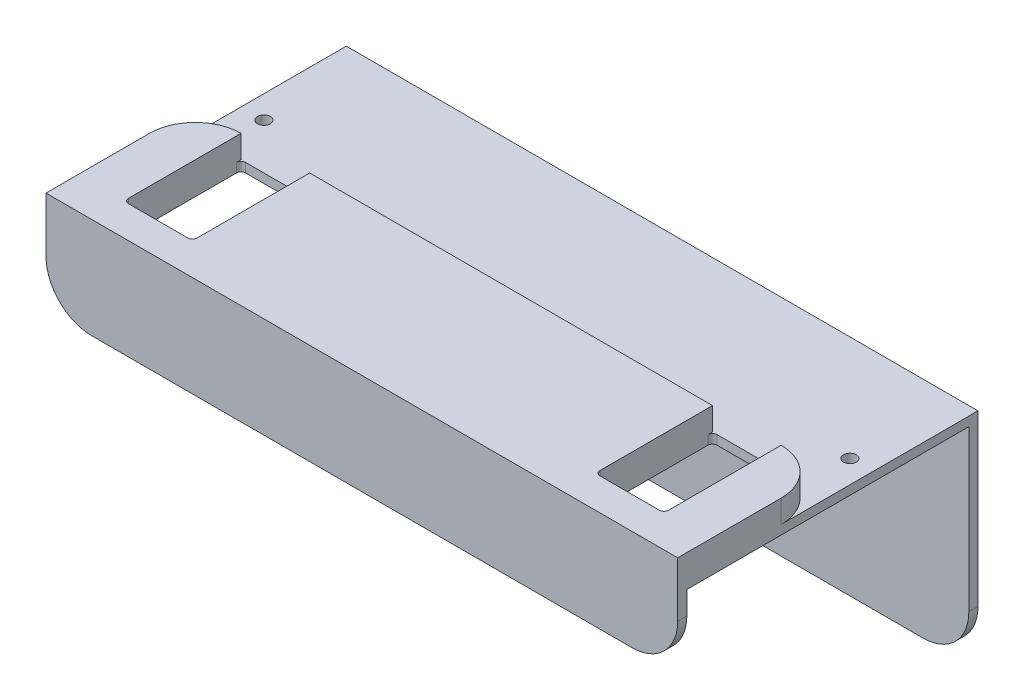
SolidWorks part; units mm, degrees
ref_plane "前视基准面" through (0, 0, 0) normal (0, 0, 1) x (1, 0, 0)
ref_plane "上视基准面" through (0, 0, 0) normal (0, 1, 0) x (1, 0, 0)
ref_plane "右视基准面" through (0, 0, 0) normal (1, 0, 0) x (0, 0, -1)
other "Configuration Table"
sketch "草图1" plane through (0, 0, 0) normal (0, 1, 0) x (1, 0, 0)
  line L0 (-64, 9.8) -> (64, 9.8) construction
  line L1 (-69, -32.8) -> (69, -32.8)
  line L2 (-69, -32.8) -> (-69, 32.8)
  line L3 (-69, 32.8) -> (69, 32.8)
  line L4 (69, -32.8) -> (69, 32.8)
  line L5 (-69, -32.8) -> (69, 32.8) construction
  line L6 (-69, 32.8) -> (69, -32.8) construction
  line L7 (0, 9.8) -> (0, 32.8) construction
  circle A0 centre (-64, 9.8) radius 1.4
  circle A1 centre (64, 9.8) radius 1.4
  point P0 (0, 0)
  dimension "D3" = 2.8
  dimension "D4" = 2.8
  dimension "D5" = 128
  dimension "D6" = 23
  dimension "D1" = 138
  dimension "D2" = 65.6
extrude "凸台-拉伸1" add sketch "草图1" along normal blind 2
sketch "草图2" plane through (0, 2, 0) normal (0, 1, 0) x (1, 0, 0)
  line L0 (69, -32.8) -> (69, 32.8) construction
  line L1 (-69, -32.8) -> (69, -32.8)
  line L2 (-69, -32.8) -> (-69, -0.2)
  line L3 (-69, -0.2) -> (69, -0.2)
  line L4 (69, -32.8) -> (69, -0.2)
  line L5 (69, 32.8) -> (-69, 32.8) construction
  dimension "D1" = 33
extrude "凸台-拉伸2" add sketch "草图2" along normal blind 5
sketch "草图3" plane through (0, 0, 0) normal (0, -1, 0) x (1, 0, 0)
  line L0 (-69, -32.8) -> (-69, 32.8) construction
  line L2 (-69, -30.8) -> (69, -30.8)
  line L3 (-69, -30.8) -> (-69, -32.8)
  line L4 (-69, -32.8) -> (69, -32.8)
  line L5 (69, -30.8) -> (69, -32.8)
  dimension "D1" = 2
extrude "凸台-拉伸3" add sketch "草图3" along normal blind 45
fillet "圆角1" radius 10 2 edges at (69, 4.5, 0.2) (-69, 4.5, 0.2)
sketch "草图5" plane through (0, 0, 0) normal (0, -1, 0) x (1, 0, 0)
  line L0 (69, 32.8) -> (69, -30.8) construction
  line L1 (-69, 32.8) -> (69, 32.8)
  line L2 (-69, 32.8) -> (-69, 30.8)
  line L3 (-69, 30.8) -> (69, 30.8)
  line L4 (69, 32.8) -> (69, 30.8)
  dimension "D1" = 2
extrude "凸台-拉伸4" add sketch "草图5" along normal blind 15
fillet "圆角2" radius 10 4 edges at (-69, -45, -31.8) (-69, -15, 31.8) (69, -45, -31.8) (69, -15, 31.8)
sketch "草图6" plane through (0, 0, 0) normal (0, -1, 0) x (1, 0, 0)
  line L1 (-59, 25.8) -> (-44, 25.8)
  line L2 (-59, 25.8) -> (-59, 0.2)
  line L3 (-59, 0.2) -> (-44, 0.2)
  line L4 (-44, 25.8) -> (-44, 0.2)
  line L6 (59, 32.8) -> (-59, 32.8) construction
  line L7 (-69, -30.8) -> (-69, 30.8) construction
  line L8 (-59, 30.8) -> (59, 30.8) construction
  line L9 (0, 46.1908) -> (0, -54.224) construction
  line L10 (59, 0.2) -> (44, 0.2)
  line L11 (44, 25.8) -> (44, 0.2)
  line L12 (59, 25.8) -> (44, 25.8)
  line L13 (59, 25.8) -> (59, 0.2)
  dimension "D1" = 32.6
  dimension "D2" = 10
  dimension "D3" = 15
  dimension "D4" = 5
extrude "切除-拉伸1" cut sketch "草图6" against normal up to surface (7 mm away) up to face at (0, 7, 13.7096)
fillet "圆角3" radius 1 4 edges at (-44, 3.5, 25.8) (-59, 3.5, 25.8) (44, 3.5, 25.8) (59, 3.5, 25.8)
fillet "圆角4" radius 1 4 edges at (59, 1, 0.2) (44, 1, 0.2) (-59, 1, 0.2) (-44, 1, 0.2)
